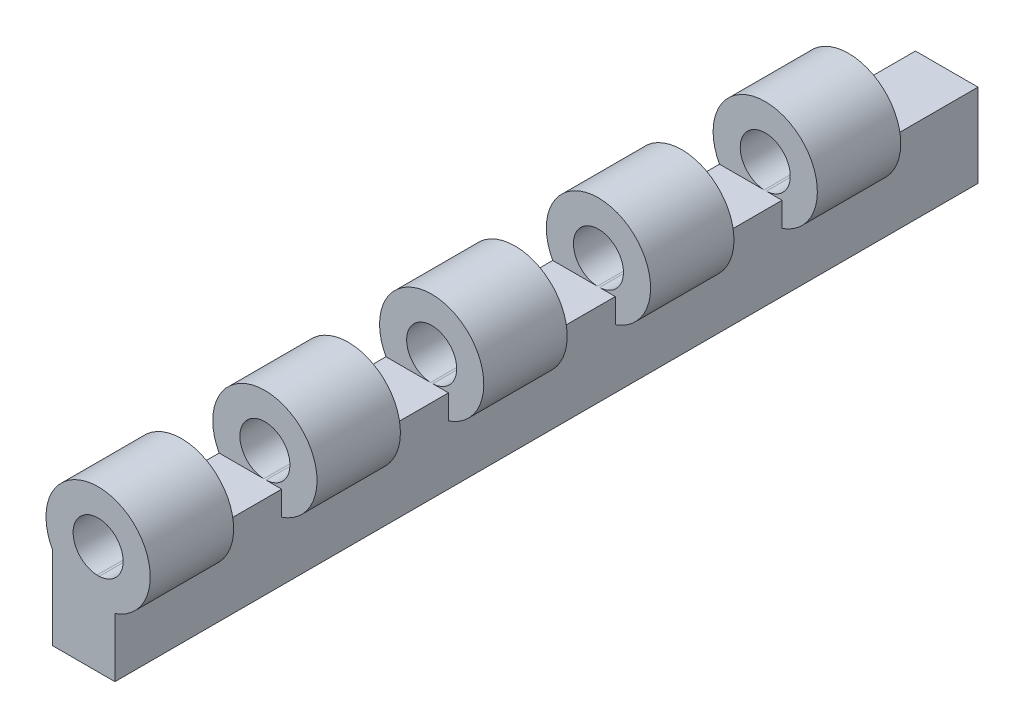
SolidWorks part; units mm, degrees
ref_plane "Front Plane" through (0, 0, 0) normal (0, 0, 1) x (1, 0, 0)
ref_plane "Top Plane" through (0, 0, 0) normal (0, 1, 0) x (1, 0, 0)
ref_plane "Right Plane" through (0, 0, 0) normal (1, 0, 0) x (0, 0, -1)
sketch "Sketch1" plane through (0, 0, 0) normal (0, 1, 0) x (1, 0, 0)
  line L0 (0, 103.5) -> (0, -103.5)
  line L1 (0, 103.5) -> (15, 103.5)
  line L2 (15, 103.5) -> (15, -103.5)
  line L3 (15, -103.5) -> (0, -103.5)
  point P4 (0, 0)
  point P8 (0, 103.5)
  dimension "D1" = 207
  dimension "D2" = 15
extrude "Boss-Extrude1" add sketch "Sketch1" along normal blind 20
ref_plane "Plane1" through (0, 0, 103.5) normal (0, 0, 1) x (1, 0, 0)
sketch "Sketch2" plane through (0, 0, 103.5) normal (0, 0, 1) x (1, 0, 0)
  circle A0 centre (10.969, 25.9942) radius 12.5
  circle A1 centre (10.969, 25.9942) radius 6
  dimension "D1" = 25
extrude "Boss-Extrude2" add sketch "Sketch2" against normal blind 20
pattern_linear "LPattern1" count 5 spacing 40 along (0, 0, -1) of "Boss-Extrude2"
